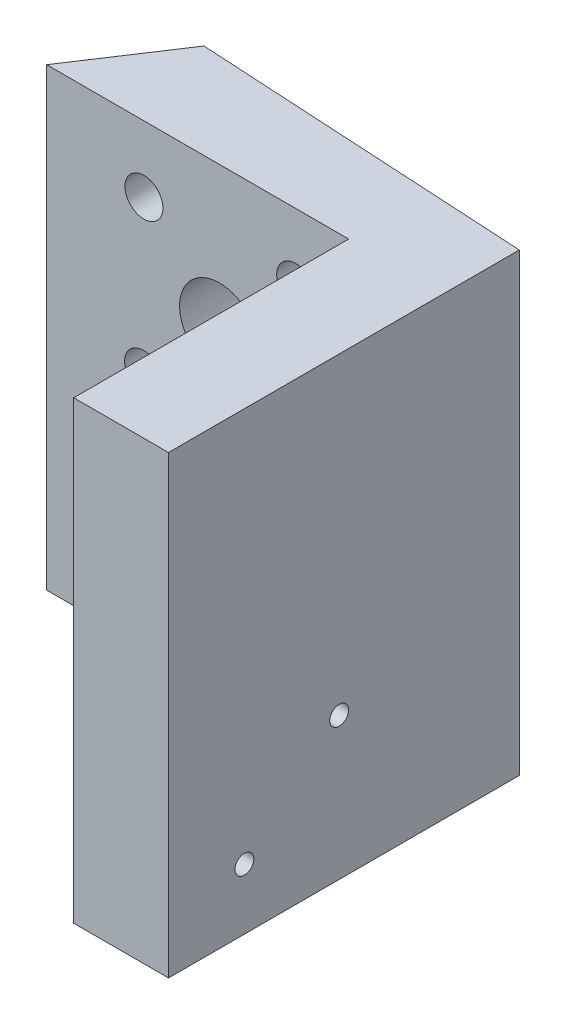
SolidWorks part; units mm, degrees
ref_plane "Front" through (0, 0, 0) normal (0, 0, 1) x (1, 0, 0)
ref_plane "Top" through (0, 0, 0) normal (0, 1, 0) x (1, 0, 0)
ref_plane "Right" through (0, 0, 0) normal (1, 0, 0) x (0, 0, -1)
sketch "Sketch1" plane through (0, 0, 0) normal (0, 1, 0) x (1, 0, 0)
  line L2 (0, 0) -> (0, -29)
  line L3 (0, -29) -> (10, -29)
  line L4 (10, 0) -> (10, -29)
  line L5 (10, 0) -> (-31.85, 0)
  line L6 (10, 0) -> (10, 10)
  line L7 (10, 10) -> (-31.85, 10)
  line L8 (-31.85, 0) -> (-31.85, 10)
  dimension "D1" = 41.85
  dimension "D2" = 29
  dimension "D3" = 10
  dimension "D4" = 10
extrude "Boss-Extrude1" add sketch "Sketch1" along normal blind 48 contours L8 L5 L6 L7 | L4 L5 L2 L3
sketch "Sketch3" plane through (0, 48, 0) normal (0, 1, 0) x (1, 0, 0)
  line L0 (-31.85, 10) -> (-25.2632, 10)
  line L1 (10, 10) -> (-31.85, 10) construction
  line L2 (-25.2632, 10) -> (-31.85, 0)
  line L3 (-31.85, 0) -> (-31.85, 10)
  dimension "D1" = 33.372
extrude "Cut-Extrude1" cut sketch "Sketch3" against normal blind 48
sketch "Sketch4" plane through (0, 0, 0) normal (0, 0, 1) x (1, 0, 0)
  circle A0 centre (-5.5896, 40.9808) radius 2
  circle A1 centre (-5.6297, 24.9791) radius 2
  circle A2 centre (-21.5913, 41.0209) radius 2
  circle A3 centre (-21.6315, 25.0192) radius 2
  circle A4 centre (-13.6297, 32.9791) radius 4.2
extrude "Cut-Extrude2" cut sketch "Sketch4" against normal blind 48
sketch "Sketch5" plane through (0, 48, 0) normal (0, 1, 0) x (1, 0, 0)
  line L0 (-25.2632, 10) -> (10, 8)
  line L1 (10, -29) -> (10, 10) construction
  line L2 (10, 8) -> (10, 10)
  line L3 (10, 10) -> (-25.2632, 10)
extrude "Cut-Extrude3" cut sketch "Sketch5" against normal blind 48
sketch "Sketch6" plane through (10, 0, 0) normal (1, 0, 0) x (0, 0, -1)
  line L0 (-29, 48) -> (-29, 0) construction
  line L1 (-29, 48) -> (-29, 0) construction
  line L2 (-29, 0) -> (8, 0) construction
  circle A0 centre (-21, 6.3919) radius 1
  circle A1 centre (-11, 15) radius 1
  dimension "D1" = 8
  dimension "D2" = 18
  dimension "D3" = 15
extrude "Cut-Extrude4" cut sketch "Sketch6" against normal blind 2
sketch "Sketch7" plane through (0.4843, 0, -8.5397) normal (0.0566, 0, -0.9984) x (-0.9984, 0, -0.0566)
  line L1 (25.7889, 0) -> (-9.531, 0) construction
  line L2 (-9.531, 0) -> (-9.531, 48) construction
  circle A0 centre (10.469, 7) radius 1
  dimension "D1" = 7
  dimension "D2" = 20
extrude "Cut-Extrude5" cut sketch "Sketch7" against normal blind 1
